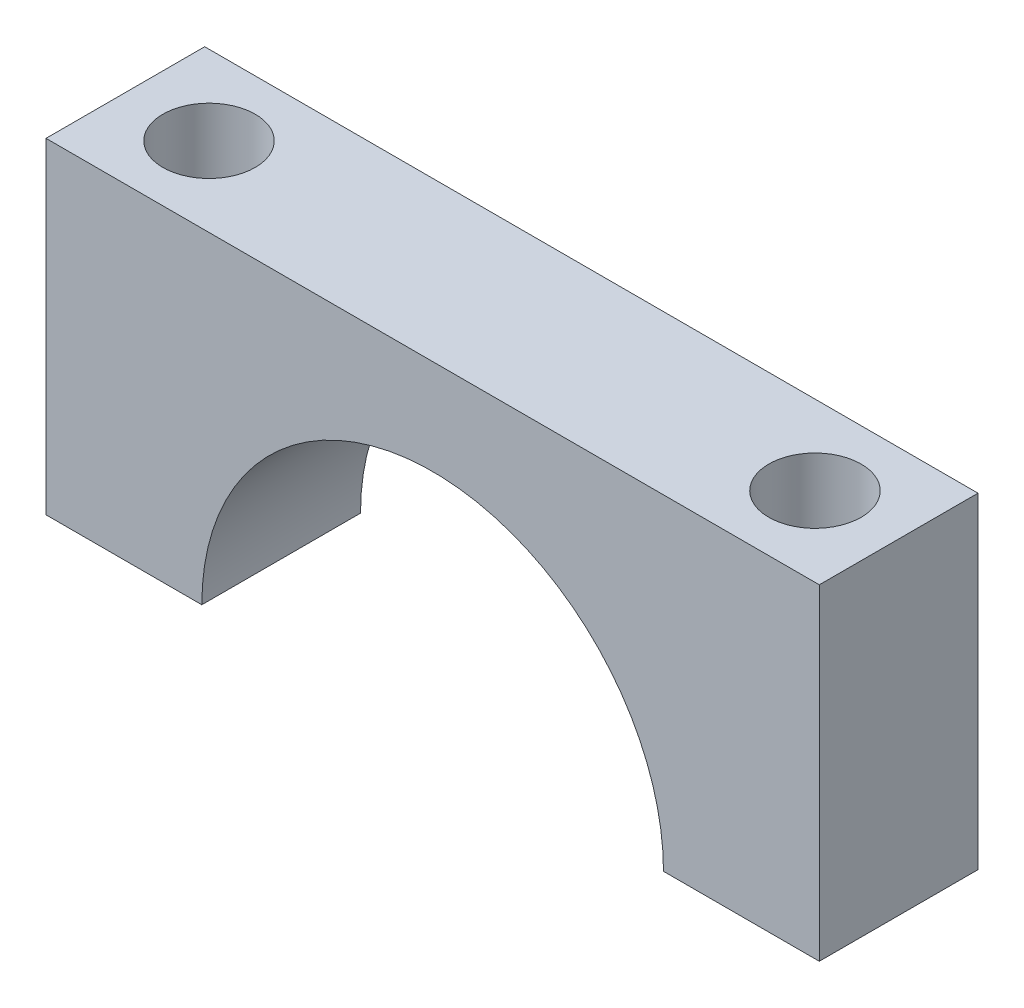
SolidWorks part; units mm, degrees
material "ABS PC"
ref_plane "Front Plane" through (0, 0, 0) normal (0, 0, 1) x (1, 0, 0)
ref_plane "Top Plane" through (0, 0, 0) normal (0, 1, 0) x (1, 0, 0)
ref_plane "Right Plane" through (0, 0, 0) normal (1, 0, 0) x (0, 0, -1)
sketch "Sketch1" plane through (0, 0, 0) normal (0, 0, 1) x (1, 0, 0)
  line L0 (55, 0) -> (-55, 0) construction
  line L1 (-13.4, 11.3) -> (13.4, 11.3)
  line L2 (-13.4, 11.3) -> (-13.4, 0)
  line L3 (-13.4, 0) -> (-8, 0)
  line L4 (13.4, 11.3) -> (13.4, 0)
  line L5 (8, 0) -> (13.4, 0)
  line L6 (0, -55) -> (0, 55) construction
  arc A0 (8, 0) -> (-8, 0) centre (0, 0) ccw
  dimension "D2" = 8
  dimension "D1" = 11.3
  dimension "D3" = 26.8
extrude "Boss-Extrude1" add sketch "Sketch1" along normal mid plane 5.5
sketch "Sketch2" plane through (0, 0, 0) normal (0, -1, 0) x (1, 0, 0)
  line L0 (6.215, 0) -> (-6.215, 0) construction
  line L1 (-10.5, 0) -> (10.5, 0) construction
  circle A0 centre (-10.5, 0) radius 1.6
  circle A1 centre (10.5, 0) radius 1.6
  point P6 (0, 0)
  dimension "D1" = 3.2
  dimension "D2" = 21
extrude "Cut-Extrude1" cut sketch "Sketch2" against normal through all
